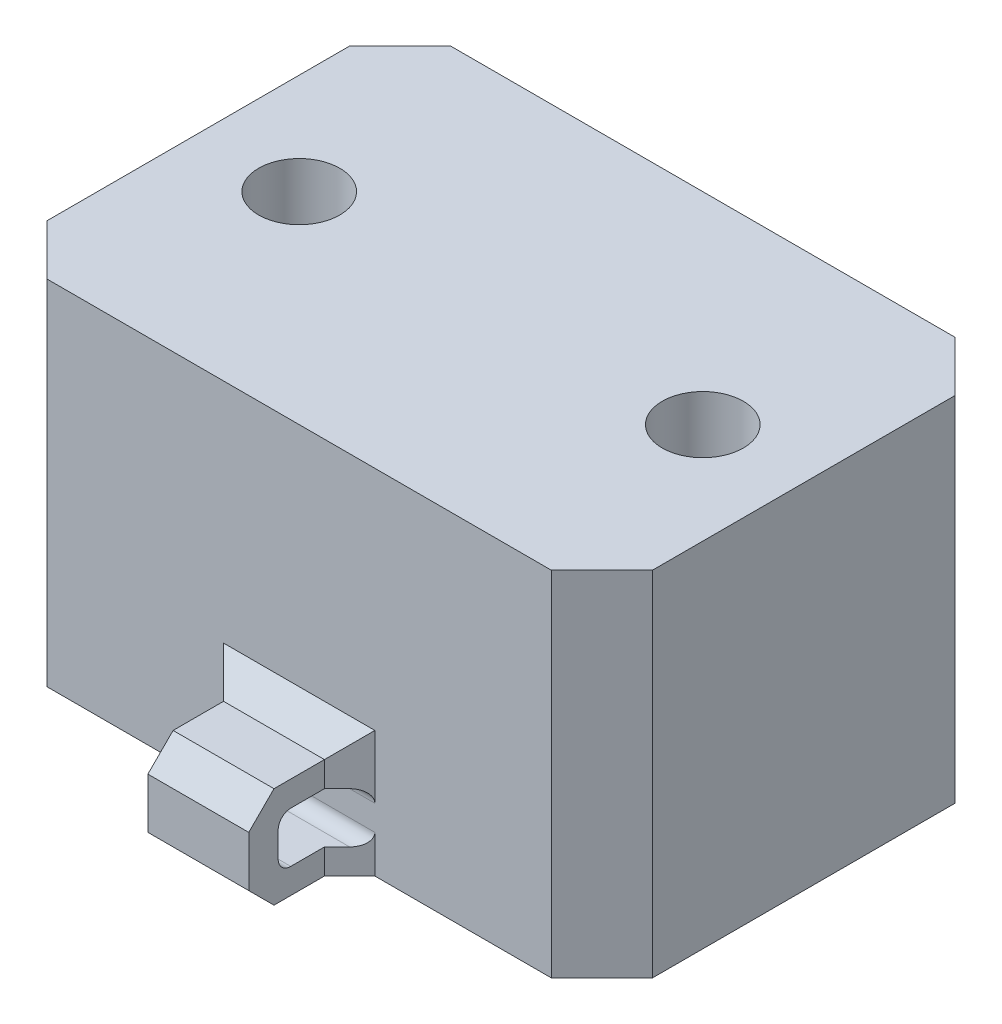
SolidWorks part; units mm, degrees
ref_plane "Front" through (0, 0, 0) normal (0, 0, 1) x (1, 0, 0)
ref_plane "Top" through (0, 0, 0) normal (0, 1, 0) x (1, 0, 0)
ref_plane "Right" through (0, 0, 0) normal (1, 0, 0) x (0, 0, -1)
sketch "Sketch1" plane through (0, 0, 0) normal (0, 1, 0) x (1, 0, 0)
  line L1 (-19.05, 12.7) -> (19.05, 12.7)
  line L2 (-19.05, 12.7) -> (-19.05, -12.7)
  line L3 (-19.05, -12.7) -> (19.05, -12.7)
  line L4 (19.05, 12.7) -> (19.05, -12.7)
  line L5 (-19.05, 12.7) -> (19.05, -12.7) construction
  line L6 (-19.05, -12.7) -> (19.05, 12.7) construction
  point P0 (0, 0)
  dimension "D1" = 25.4
  dimension "D2" = 38.1
extrude "Boss-Extrude1" add sketch "Sketch1" along normal blind 22.225
hole_wizard "#10 Clearance Hole1" positions "Sketch2" profile "Sketch3" hole size "#10" standard "ANSI Inch" end condition through all
sketch "Sketch2" plane through (0, 22.225, 0) normal (0, 1, 0) x (1, 0, 0)
  line L2 (12.7, 0) -> (-12.7, 0)
  point P0 (-12.7, 0)
  point P2 (12.7, 0)
  dimension "D1" = 25.4
sketch "Sketch3" plane through (-12.7, 22.225, 0) normal (1, 0, 0) x (0, 0, 1)
  line L0 (0, 0) -> (0, 22.225)
  line L1 (0, 22.225) -> (2.5527, 22.225)
  line L2 (2.5527, 22.225) -> (2.5527, 0)
  line L5 (2.5527, 0) -> (0, 0)
  line L11 (0, -6.35) -> (0, 107.95) construction
  dimension "Thru Hole Dia." = 5.1054
  dimension "Thru Hole Depth" = 22.225
chamfer "Chamfer1" distance 3.175 angle 45 4 edges at (-19.05, 11.1125, -12.7) (-19.05, 11.1125, 12.7) (19.05, 11.1125, -12.7) (19.05, 11.1125, 12.7)
sketch "Sketch6" plane through (0, 0, 12.7) normal (0, 0, 1) x (1, 0, 0)
  line L0 (-15.875, 0) -> (15.875, 0) construction
  line L1 (-3.175, 6.35) -> (3.175, 6.35)
  line L2 (-3.175, 6.35) -> (-3.175, 0)
  line L3 (-3.175, 0) -> (3.175, 0)
  line L4 (3.175, 6.35) -> (3.175, 0)
  point P6 (0, 0)
  dimension "D1" = 6.35
  dimension "D2" = 6.35
extrude "Boss-Extrude3" add sketch "Sketch6" along normal blind 6.35
sketch "Sketch7" plane through (-3.175, 0, 0) normal (-1, 0, 0) x (0, 0, 1)
  line L1 (17.2, 4.7625) -> (12.7, 4.7625)
  line L2 (17.2, 4.7625) -> (17.2, 1.5875)
  line L3 (17.2, 1.5875) -> (12.7, 1.5875)
  line L4 (12.7, 4.7625) -> (12.7, 1.5875)
  line L5 (12.7, 6.35) -> (12.7, 0) construction
  line L6 (19.05, 6.35) -> (19.05, 0) construction
  point P5 (12.7, 1.3664)
  point P6 (12.7, 4.8139)
  point P8 (12.7, 3.175)
  point P9 (19.05, 3.175)
  point P12 (17.2, 3.175)
  dimension "D1" = 3.175
  dimension "D2" = 4.5
extrude "Cut-Extrude1" cut sketch "Sketch7" against normal up to next
chamfer "Chamfer4" distance 1.5875 angle 45 2 edges at (0, 6.35, 19.05) (0, 0, 19.05)
chamfer "Chamfer5" distance 1.5875 angle 45 5 edges at (3.175, 0.7938, 12.7) (-3.175, 0.7938, 12.7) (3.175, 5.5563, 12.7) (0, 6.35, 12.7) (-3.175, 5.5563, 12.7)
fillet "Fillet2" radius 0.7937 4 edges at (0, 1.5875, 12.7) (0, 4.7625, 12.7) (0, 1.5875, 17.2) (0, 4.7625, 17.2)
